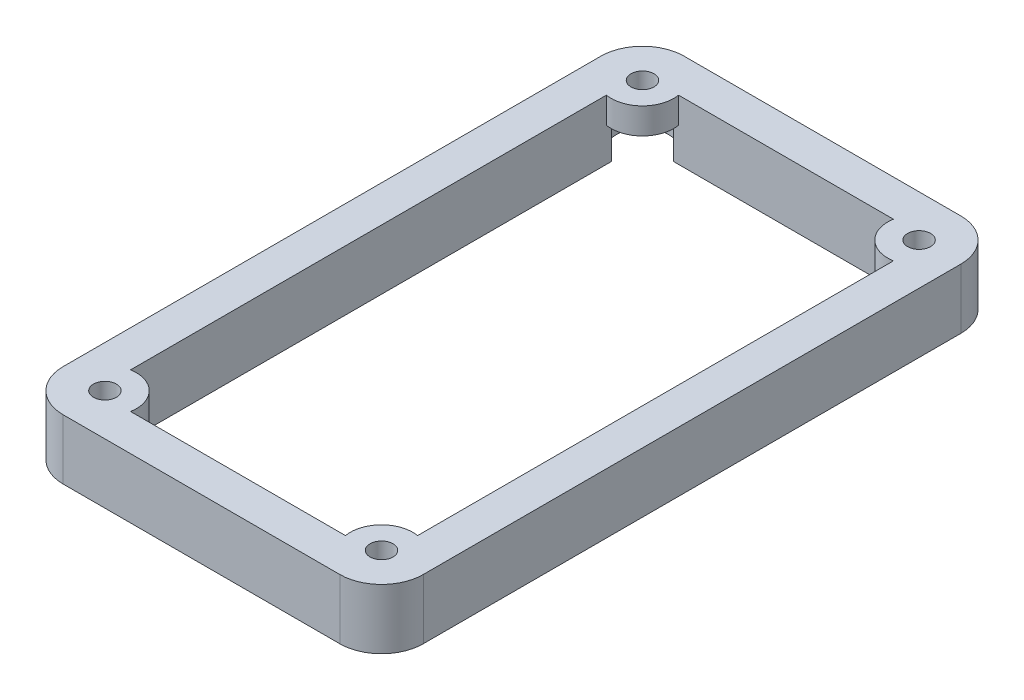
SolidWorks part; units mm, degrees
ref_plane "Front Plane" through (0, 0, 0) normal (0, 0, 1) x (1, 0, 0)
ref_plane "Top Plane" through (0, 0, 0) normal (0, 1, 0) x (1, 0, 0)
ref_plane "Right Plane" through (0, 0, 0) normal (1, 0, 0) x (0, 0, -1)
sketch "Sketch1" plane through (0, 0, 0) normal (0, 1, 0) x (1, 0, 0)
  line L1 (-32.5, -57.5) -> (32.5, -57.5)
  line L2 (-32.5, -57.5) -> (-32.5, 57.5)
  line L3 (-32.5, 57.5) -> (32.5, 57.5)
  line L4 (32.5, -57.5) -> (32.5, 57.5)
  line L5 (0, 57.5) -> (0, -57.5) construction
  line L6 (-32.5, 0) -> (32.5, 0) construction
  line L7 (-27.5, 52.5) -> (27.5, 52.5)
  line L8 (-27.5, 52.5) -> (-27.5, -52.5)
  line L9 (-27.5, -52.5) -> (27.5, -52.5)
  line L10 (27.5, 52.5) -> (27.5, -52.5)
  line L11 (0, -52.5) -> (0, 52.5) construction
  line L12 (-27.5, 0) -> (27.5, 0) construction
  point P0 (0, 0)
  point P4 (0, 0)
  dimension "D1" = 115
  dimension "D2" = 65
  dimension "D3" = 5
  dimension "D4" = 5
extrude "Boss-Extrude1" add sketch "Sketch1" along normal blind 23
fillet "Fillet1" radius 6 4 edges at (32.5, 11.5, -57.5) (-32.5, 11.5, -57.5) (-32.5, 11.5, 57.5) (32.5, 11.5, 57.5)
sketch "Sketch2" plane through (0, 23, 0) normal (0, 1, 0) x (1, 0, 0)
  circle A0 centre (-26.5, 51.5) radius 6
  circle A1 centre (26.5, 51.5) radius 6
  circle A2 centre (-26.5, -51.5) radius 6
  circle A3 centre (26.5, -51.5) radius 6
  dimension "D1" = 12
extrude "Boss-Extrude2" add sketch "Sketch2" against normal up to surface (23 mm away) up to face at (0, 0, 0)
sketch "Sketch4" plane through (0, 23, 0) normal (0, 1, 0) x (1, 0, 0)
  circle A0 centre (-26.5, 51.5) radius 2.2
  circle A1 centre (26.5, 51.5) radius 2.2
  circle A2 centre (26.5, -51.5) radius 2.2
  circle A3 centre (-26.5, -51.5) radius 2.2
  dimension "D1" = 4.4
extrude "Cut-Extrude1" cut sketch "Sketch4" against normal blind 23
ref_plane "Plane1" through (0, 18, 0) normal (0, 1, 0) x (1, 0, 0)
sketch "Sketch7" plane through (0, 18, 0) normal (0, 1, 0) x (1, 0, 0)
  line L1 (27.5, -52.5) -> (-27.5, -52.5)
  line L2 (27.5, -52.5) -> (27.5, 52.5)
  line L3 (27.5, 52.5) -> (-27.5, 52.5)
  line L4 (-27.5, -52.5) -> (-27.5, 52.5)
  line L5 (0, 52.5) -> (0, -52.5) construction
  line L6 (27.5, 0) -> (-27.5, 0) construction
  point P0 (0, 0)
extrude "Cut-Extrude2" cut sketch "Sketch7" against normal blind 13
sketch "Sketch8" plane through (0, 0, 57.5) normal (0, 0, 1) x (1, 0, 0)
  line L0 (-32.5, 0) -> (-32.5, 23) construction
  line L1 (-32.5, 11.5) -> (32.5, 11.5)
  line L2 (-32.5, 11.5) -> (-32.5, 0)
  line L3 (-32.5, 0) -> (32.5, 0)
  line L4 (32.5, 11.5) -> (32.5, 0)
extrude "Cut-Extrude3" cut sketch "Sketch8" against normal blind 120
sketch "Sketch9" plane through (0, 18, 0) normal (0, -1, 0) x (1, 0, 0)
  circle A0 centre (-26.5, -51.5) radius 5
  circle A1 centre (26.5, -51.5) radius 5
  circle A2 centre (26.5, 51.5) radius 5
  circle A3 centre (-26.5, 51.5) radius 5
  dimension "D1" = 10
extrude "Cut-Extrude4" cut sketch "Sketch9" along normal up to surface (6.5 mm away) up to face at (0, 11.5, 0)
sketch "Sketch10" plane through (0, 23, 0) normal (0, 1, 0) x (1, 0, 0)
  line L20 (-26.5, -57.5) -> (26.5, -57.5) construction
  line L21 (32.5, -51.5) -> (32.5, 51.5) construction
  line L22 (26.5, 57.5) -> (-26.5, 57.5) construction
  line L23 (-32.5, 51.5) -> (-32.5, -51.5) construction
  line L24 (-26.5, -59.5) -> (26.5, -59.5)
  line L25 (34.5, -51.5) -> (34.5, 51.5)
  line L26 (26.5, 59.5) -> (-26.5, 59.5)
  line L27 (-34.5, 51.5) -> (-34.5, -51.5)
  line L28 (-26.5, -59.5) -> (26.5, -59.5)
  line L29 (34.5, -51.5) -> (34.5, 51.5)
  line L30 (26.5, 59.5) -> (-26.5, 59.5)
  line L31 (-34.5, 51.5) -> (-34.5, -51.5)
  line L32 (-26.5, -57.5) -> (26.5, -57.5)
  line L33 (32.5, -51.5) -> (32.5, 51.5)
  line L34 (26.5, 57.5) -> (-26.5, 57.5)
  line L35 (-32.5, 51.5) -> (-32.5, -51.5)
  arc A16 (-32.5, -51.5) -> (-26.5, -57.5) centre (-26.5, -51.5) ccw construction
  arc A17 (26.5, -57.5) -> (32.5, -51.5) centre (26.5, -51.5) ccw construction
  arc A18 (32.5, 51.5) -> (26.5, 57.5) centre (26.5, 51.5) ccw construction
  arc A19 (-26.5, 57.5) -> (-32.5, 51.5) centre (-26.5, 51.5) ccw construction
  arc A20 (-34.5, -51.5) -> (-26.5, -59.5) centre (-26.5, -51.5) ccw
  arc A21 (26.5, -59.5) -> (34.5, -51.5) centre (26.5, -51.5) ccw
  arc A22 (34.5, 51.5) -> (26.5, 59.5) centre (26.5, 51.5) ccw
  arc A23 (-26.5, 59.5) -> (-34.5, 51.5) centre (-26.5, 51.5) ccw
  arc A24 (-34.5, -51.5) -> (-26.5, -59.5) centre (-26.5, -51.5) ccw
  arc A25 (26.5, -59.5) -> (34.5, -51.5) centre (26.5, -51.5) ccw
  arc A26 (34.5, 51.5) -> (26.5, 59.5) centre (26.5, 51.5) ccw
  arc A27 (-26.5, 59.5) -> (-34.5, 51.5) centre (-26.5, 51.5) ccw
  arc A28 (-32.5, -51.5) -> (-26.5, -57.5) centre (-26.5, -51.5) ccw
  arc A29 (26.5, -57.5) -> (32.5, -51.5) centre (26.5, -51.5) ccw
  arc A30 (32.5, 51.5) -> (26.5, 57.5) centre (26.5, 51.5) ccw
  arc A31 (-26.5, 57.5) -> (-32.5, 51.5) centre (-26.5, 51.5) ccw
  dimension "D1" = 2
extrude "Boss-Extrude3" add sketch "Sketch10" against normal up to surface (11.5 mm away) up to face at (0, 11.5, 0)
